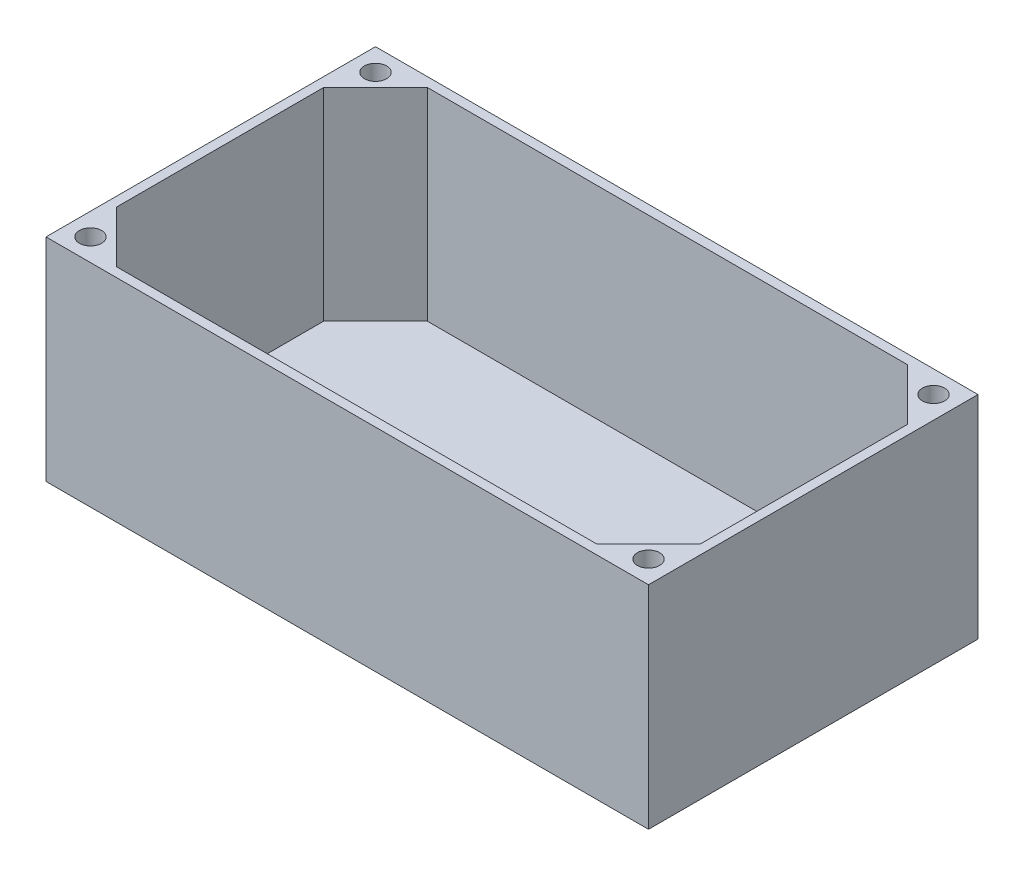
SolidWorks part; units mm, degrees
ref_plane "Front Plane" through (0, 0, 0) normal (0, 0, 1) x (1, 0, 0)
ref_plane "Top Plane" through (0, 0, 0) normal (0, 1, 0) x (1, 0, 0)
ref_plane "Right Plane" through (0, 0, 0) normal (1, 0, 0) x (0, 0, -1)
sketch "Sketch1" plane through (0, 0, 0) normal (0, 1, 0) x (1, 0, 0)
  line L1 (0, 0) -> (81.28, 0)
  line L2 (0, 0) -> (0, 44.45)
  line L3 (0, 44.45) -> (81.28, 44.45)
  line L4 (81.28, 0) -> (81.28, 44.45)
  dimension "D1" = 81.28
  dimension "D2" = 44.45
extrude "Boss-Extrude1" add sketch "Sketch1" along normal blind 28.575
shell "Shell1" thickness 1.27
chamfer "Chamfer1" distance 6.985 angle 45 4 edges at (1.27, 14.9225, -1.27) (80.01, 14.9225, -1.27) (80.01, 14.9225, -43.18) (1.27, 14.9225, -43.18)
sketch "Sketch2" plane through (0, 28.575, 0) normal (0, 1, 0) x (1, 0, 0)
  line L0 (0, 0) -> (81.28, 0) construction
  line L1 (81.28, 0) -> (81.28, 44.45) construction
  line L2 (81.28, 44.45) -> (0, 44.45) construction
  line L3 (0, 44.45) -> (0, 0) construction
  circle A0 centre (3, 41.45) radius 1.5
  circle A1 centre (3, 3) radius 1.5
  circle A2 centre (78.28, 3) radius 1.5
  circle A3 centre (78.28, 41.45) radius 1.5
  point P8 (0, 0)
  point P9 (0, 0)
  point P10 (0, 0)
  point P11 (0, 0)
  point P12 (0, 0)
  dimension "D2" = 3
  dimension "D3" = 3
  dimension "D4" = 3
  dimension "D5" = 3
  dimension "D1" = 3
  dimension "D6" = 3
  dimension "D7" = 3
  dimension "D8" = 3
extrude "Cut-Extrude1" cut sketch "Sketch2" against normal through all
sketch "Sketch3" plane through (0, 1.27, 0) normal (0, 1, 0) x (1, 0, 0)
  line L0 (1.27, 36.195) -> (1.27, 8.255) construction
  line L1 (73.025, 43.18) -> (8.255, 43.18) construction
  line L2 (0, 44.45) -> (0, 0) construction
  line L7 (5.62, 28.225) -> (9.62, 28.225)
  line L8 (5.62, 28.225) -> (5.62, 16.225)
  line L9 (5.62, 16.225) -> (9.62, 16.225)
  line L10 (9.62, 28.225) -> (9.62, 16.225)
  line L11 (5.62, 28.225) -> (9.62, 16.225) construction
  line L12 (5.62, 16.225) -> (9.62, 28.225) construction
  line L13 (32.258, 28.321) -> (49.022, 28.321)
  line L14 (32.258, 28.321) -> (32.258, 16.129)
  line L15 (32.258, 16.129) -> (49.022, 16.129)
  line L16 (49.022, 28.321) -> (49.022, 16.129)
  line L17 (32.258, 28.321) -> (49.022, 16.129) construction
  line L18 (32.258, 16.129) -> (49.022, 28.321) construction
  line L19 (8.255, 1.27) -> (73.025, 1.27) construction
  circle A0 centre (67.31, 31.75) radius 3.175
  circle A2 centre (67.31, 18.415) radius 4.445
  point P2 (40.64, 22.225)
  point P6 (0, 0)
  point P11 (7.62, 22.225)
  point P18 (0, 0)
  dimension "D3" = 6.35
  dimension "D4" = 8.89
  dimension "D1" = 66.04
  dimension "D2" = 17.145
  dimension "D5" = 13.335
  dimension "D6" = 12
  dimension "D7" = 4
  dimension "D8" = 20.955
  dimension "D9" = 6.35
  dimension "D10" = 16.764
  dimension "D11" = 12.192
  dimension "D12" = 40.64
extrude "Cut-Extrude2" cut sketch "Sketch3" against normal through all
sketch "Sketch4" plane through (0, 1.27, 0) normal (0, 1, 0) x (1, 0, 0)
  circle A1 centre (67.31, 18.415) radius 5.715
  circle A3 centre (67.31, 31.75) radius 4.445
  circle A4 centre (67.31, 31.75) radius 3.175
  circle A5 centre (67.31, 18.415) radius 4.445
  dimension "D1" = 8.89
  dimension "D2" = 11.43
  dimension "D3" = 8.89
  dimension "D4" = 6.35
extrude "Boss-Extrude2" add sketch "Sketch4" along normal blind 8.89
